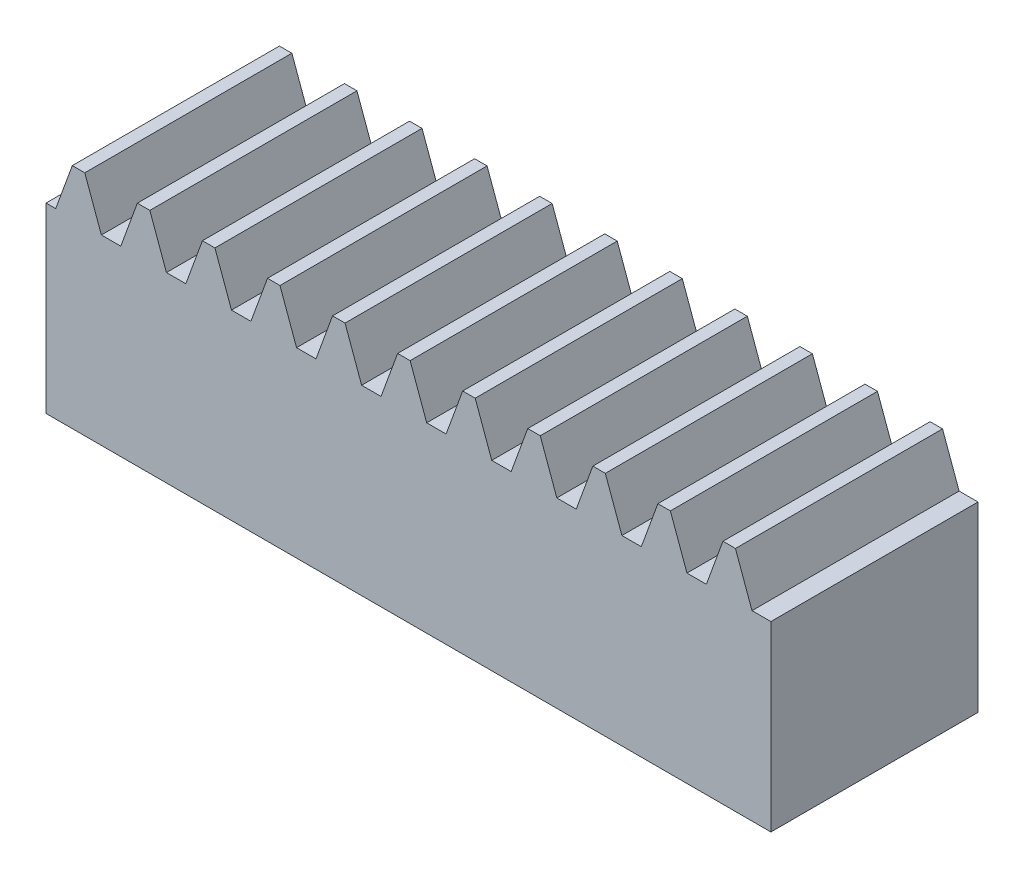
SolidWorks part; units mm, degrees
ref_plane "Plane1" through (0, 0, 0) normal (0, 0, 1) x (1, 0, 0)
ref_plane "Plane2" through (0, 0, 0) normal (0, 1, 0) x (1, 0, 0)
ref_plane "Plane3" through (0, 0, 0) normal (1, 0, 0) x (0, 0, -1)
sketch "HoldingSke" plane through (0, 0, 0) normal (0, 1, 0) x (1, 0, 0)
  line L0 (0, 0) -> (389.1506, -326.5361)
  line L1 (-15, 0) -> (100, 0) construction
  line L2 (0, 0) -> (-2.1039, 2.3779)
  line L3 (0, 0) -> (-11.863, 4.5341)
  line L4 (0, 0) -> (8.4147, 1.9427)
  line L5 (0, 0) -> (-23.7986, -8.8762)
  line L6 (0, 0) -> (-10.5278, -7.1032)
  line L9 (-71.009, 38.7566) -> (-29.2396, 53.9594)
  line L10 (-76.2, 71.12) -> (-63.5, 71.12)
  line L11 (0, 0) -> (-12.7, 0)
  line L12 (-76.2, 101.6) -> (-76.1492, 101.6)
  line L13 (24.9733, 27.94) -> (52.9518, 28.4284)
  line L14 (24.9733, 27.94) -> (25.0241, 27.9398)
  line L15 (24.9733, 27.94) -> (100.4021, 29.52)
  circle A0 centre (0, 0) radius 19.05
  circle A1 centre (0, 0) radius 6.35
  circle A2 centre (0, 0) radius 12.7
  dimension "MPH" = 12.7
  dimension "Diameter" = 38.1
  dimension "Num_teeth" = 13
  dimension "Pitch" = 508
  dimension "Width" = 12.7
  dimension "Show_teeth" = 400
  dimension "Thickness" = 12.7
  dimension "Ap" = 20
  dimension "Pitch_height" = 12.7
  dimension "Backlash" = 0.0508
  dimension "Addendum_fac" = 1
  dimension "Dedendum_fac" = 1.2
  dimension "Clearance_fac" = 0.2
  dimension "Dedendum_add" = 0.0508
  dimension "Length" = 44.45
sketch "BlankSke" plane through (0, 0, 0) normal (0, 0, 1) x (1, 0, 0)
  line L1 (0, 0) -> (44.45, 0)
  line L2 (0, 0) -> (0, 13.97)
  line L3 (0, 13.97) -> (44.45, 13.97)
  line L4 (44.45, 0) -> (44.45, 13.97)
  dimension "Length" = 44.45
  dimension "Blank_height" = 13.97
extrude "Blank" add sketch "BlankSke" against normal blind 12.7
sketch "TooCutSkeIll" plane through (0, 0, 0) normal (0, 0, 1) x (1, 0, 0)
  line L0 (-1.5999, 13.9366) -> (-0.6682, 11.3766)
  line L1 (-0.3817, 11.176) -> (0.3817, 11.176)
  line L2 (0.6682, 11.3766) -> (1.5999, 13.9366)
  line L3 (44.45, 13.97) -> (0, 13.97) construction
  line L4 (0, 0) -> (0, 64.897) construction
  line L5 (-13.208, 12.7) -> (12.954, 12.7) construction
  line L6 (0, 0) -> (44.45, 0) construction
  line L7 (1.1499, 12.7) -> (1.1499, 48.7463) construction
  line L8 (-1.1499, 12.7) -> (-1.1499, 48.7463) construction
  line L9 (1.6477, 13.97) -> (1.6477, 13.9954)
  line L10 (-1.6477, 13.97) -> (-1.6477, 13.9954)
  line L11 (-1.6477, 13.9954) -> (1.6477, 13.9954)
  arc A0 (0.3817, 11.176) -> (0.6682, 11.3766) centre (0.3817, 11.4808) ccw
  arc A1 (-0.6682, 11.3766) -> (-0.3817, 11.176) centre (-0.3817, 11.4808) ccw
  arc A2 (1.6477, 13.97) -> (1.5999, 13.9366) centre (1.6477, 13.9192) ccw
  arc A3 (-1.5999, 13.9366) -> (-1.6477, 13.97) centre (-1.6477, 13.9192) ccw
  dimension "Root_fillet" = 0.3048
  dimension "Break_rad" = 0.0508
  dimension "Pitch_height" = 12.7
  dimension "Gap_width" = 2.2997
  dimension "Dedendum" = 1.524
  dimension "Addendum_plus" = 1.2954
  dimension "Pressure_angle" = 20
extrude "ToothCutIll" [suppressed] cut sketch "TooCutSkeIll" against normal through all
sketch "TooCutSkeSim" plane through (0, 0, 0) normal (0, 0, 1) x (1, 0, 0)
  line L0 (0.5952, 11.176) -> (-0.5952, 11.176)
  line L1 (1.6213, 13.9954) -> (0.5952, 11.176)
  line L2 (0, 17.4625) -> (0, 53.467) construction
  line L3 (1.6213, 13.9954) -> (-1.6213, 13.9954)
  line L6 (-1.6213, 13.9954) -> (-0.5952, 11.176)
  line L9 (-1.1499, 12.7) -> (1.1499, 12.7) construction
  line L10 (0, 0) -> (44.45, 0) construction
  line L11 (1.1499, 12.7) -> (1.1499, 53.467) construction
  line L12 (-1.1499, 12.7) -> (-1.1499, 53.467) construction
  dimension "Pitch_height" = 12.7
  dimension "Pressure_angle" = 20
  dimension "Gap_width" = 2.2997
  dimension "Dedendum" = 1.524
  dimension "Addendum_plus" = 1.2954
extrude "ToothCutSim" cut sketch "TooCutSkeSim" against normal through all
pattern_linear "TeethCuts" count 12 spacing 3.9898 along (1, 0, 0) of "ToothCutIll", "ToothCutSim"
equation "' \"Pitch@HoldingSke\" = 4"
equation "' \"Num_teeth@HoldingSke\" = 12"
equation "' \"Ap@HoldingSke\" =  20"
equation "' \"Width@HoldingSke\" = 0.25"
equation "' \"Show_teeth@HoldingSke\" = 500"
equation "' \"Backlash@HoldingSke\" = 0.009"
equation "' \"Addendum_fac@HoldingSke\" = 1.0"
equation "' \"Dedendum_fac@HoldingSke\" = 1.25"
equation "' \"Dedendum_add@HoldingSke\" = 0.00005"
equation "' \"Clearance_fac@HoldingSke\" = 0.25"
equation "' \"Pitch_height@HoldingSke\" = 1"
equation "' \"Length@HoldingSke\" = 4.71"
equation "\"MPH@HoldingSke\" = \"Dedendum_fac@HoldingSke\" / \"Pitch@HoldingSke\" + 2 * \"Dedendum_add@HoldingSke\" + 0.002"
equation "\"MPH@HoldingSke\" = ((sgn( \"MPH@HoldingSke\" - \"Pitch_height@HoldingSke\")+1)*( \"MPH@HoldingSke\" - \"Pitch_height@HoldingSke\"))/2 + \"Pitch_height@HoldingSke\""
equation "\"Blank_height@BlankSke\" = \"Pitch_height@HoldingSke\" + \"Addendum_fac@HoldingSke\"  / \"Pitch@HoldingSke\" "
equation "\"Length@BlankSke\" =  \"Length@HoldingSke\""
equation "\"Face_width@Blank\" = \"Width@HoldingSke\""
equation "\"Pressure_angle@TooCutSkeIll\" = \"Ap@HoldingSke\""
equation "\"Addendum_plus@TooCutSkeIll\" =  \"Addendum_fac@HoldingSke\"  / \"Pitch@HoldingSke\" + 0.001"
equation "\"Dedendum@TooCutSkeIll\" = \"Dedendum_fac@HoldingSke\"  / \"Pitch@HoldingSke\""
equation "\"Pitch_height@TooCutSkeIll\" =  \"MPH@HoldingSke\""
equation "\"Gap_width@TooCutSkeIll\" = 3.14159265 / 2 / \"Pitch@HoldingSke\" + 6 * \"Backlash@HoldingSke\""
equation "\"Pressure_angle@TooCutSkeSim\" = \"Ap@HoldingSke\""
equation "\"Addendum_plus@TooCutSkeSim\" =  \"Addendum_fac@HoldingSke\"  / \"Pitch@HoldingSke\" + 0.001"
equation "\"Dedendum@TooCutSkeSim\" = \"Dedendum_fac@HoldingSke\"  / \"Pitch@HoldingSke\""
equation "\"Pitch_height@TooCutSkeSim\" =  \"MPH@HoldingSke\""
equation "\"Gap_width@TooCutSkeSim\" = 3.14159265 / 2 / \"Pitch@HoldingSke\" + 6 * \"Backlash@HoldingSke\""
equation "\"Root_fillet@TooCutSkeIll\" = \"Clearance_fac@HoldingSke\" / \"Pitch@HoldingSke\" + \"Dedendum_add@HoldingSke\""
equation "\"Break_rad@TooCutSkeIll\" = 0.02 / \"Pitch@HoldingSke\" * 2"
equation "\"Linear_pitch@TeethCuts\" = 3.14159265 / \"Pitch@HoldingSke\""
equation "\"Num_teeth@HoldingSke\" = int( ( \"Length@HoldingSke\" + 0 ) / (3.14159265 / \"Pitch@HoldingSke\")) + 0.9999  + 1"
equation " \"Num_teeth@TeethCuts\" = int( \"Show_teeth@HoldingSke\" ) + 1"
equation " \"Num_teeth@TeethCuts\" = ((sgn( \"Num_teeth@TeethCuts\" - \"Num_teeth@HoldingSke\" )-1)*( \"Num_teeth@TeethCuts\" - \"Num_teeth@HoldingSke\" ))/-2+ \"Num_teeth@HoldingSke\""
equation " \"Num_teeth@TeethCuts\" = ((sgn( \"Num_teeth@TeethCuts\" - 2.0)+1)*( \"Num_teeth@TeethCuts\" - 2.0))/2 +2.0"
